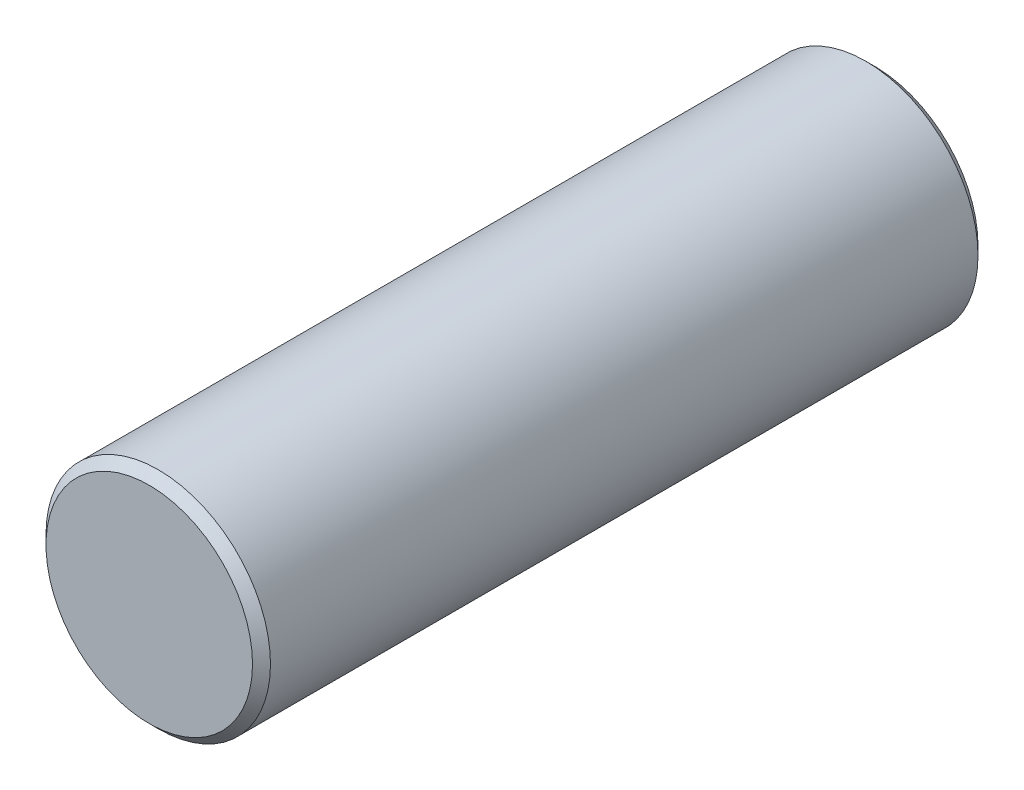
SolidWorks part; units mm, degrees
ref_plane "Front Plane" through (0, 0, 0) normal (0, 0, 1) x (1, 0, 0)
ref_plane "Top Plane" through (0, 0, 0) normal (0, 1, 0) x (1, 0, 0)
ref_plane "Right Plane" through (0, 0, 0) normal (1, 0, 0) x (0, 0, -1)
sketch "Sketch1" plane through (0, 0, 0) normal (0, 0, 1) x (1, 0, 0)
  circle A0 centre (0, 0) radius 2.5
  dimension "D1" = 5
extrude "Boss-Extrude1" add sketch "Sketch1" along normal mid plane 16.16
chamfer "Chamfer1" distance 0.2 angle 45 2 edges at (2.5, 0, -8.08) (2.5, 0, 8.08)
